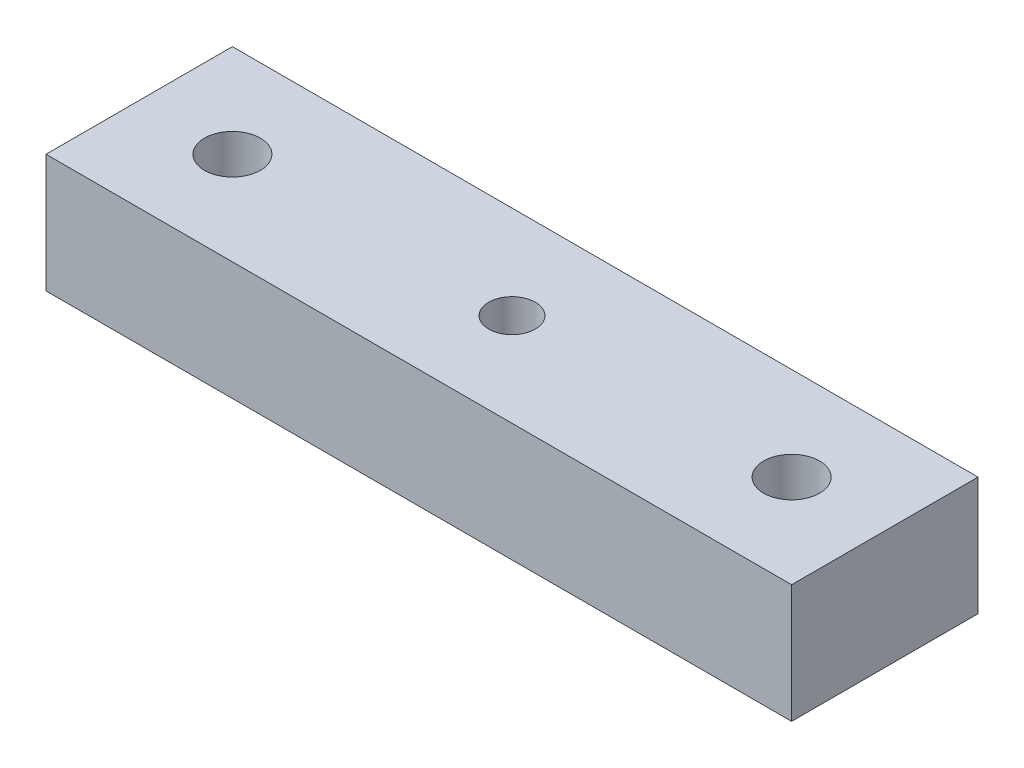
SolidWorks part; units mm, degrees
ref_plane "Front Plane" through (0, 0, 0) normal (0, 0, 1) x (1, 0, 0)
ref_plane "Top Plane" through (0, 0, 0) normal (0, 1, 0) x (1, 0, 0)
ref_plane "Right Plane" through (0, 0, 0) normal (1, 0, 0) x (0, 0, -1)
other "Default"
sketch "Sketch1" plane through (0, 0, 0) normal (0, 1, 0) x (1, 0, 0)
  line L0 (-30, 0) -> (30, 0) construction
  line L1 (-40, -10) -> (40, -10)
  line L2 (-40, -10) -> (-40, 10)
  line L3 (-40, 10) -> (40, 10)
  line L4 (40, -10) -> (40, 10)
  line L5 (-40, -10) -> (40, 10) construction
  line L6 (-40, 10) -> (40, -10) construction
  circle A0 centre (0, 0) radius 2.5
  circle A1 centre (-30, 0) radius 3
  circle A2 centre (30, 0) radius 3
  point P0 (0, 0)
  dimension "AxleDiameter" = 5
  dimension "MountingDiameter" = 6
  dimension "Width" = 20
  dimension "Length" = 80
  dimension "MountingSeparation" = 60
extrude "Boss-Extrude1" add sketch "Sketch1" along normal mid plane 12.7
